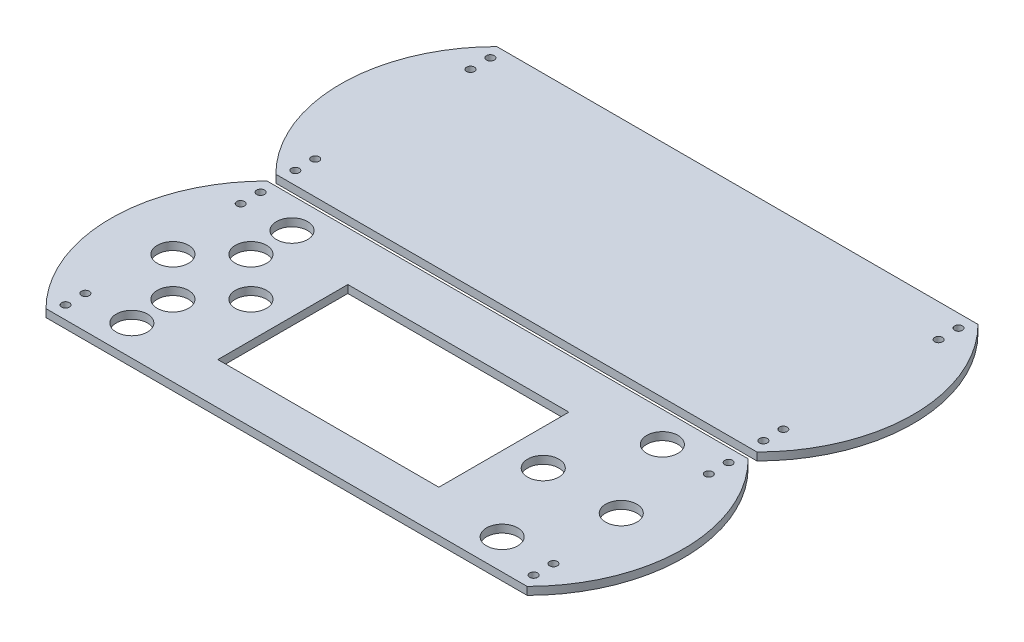
SolidWorks part; units mm, degrees
ref_plane "Front Plane" through (0, 0, 0) normal (0, 0, 1) x (1, 0, 0)
ref_plane "Top Plane" through (0, 0, 0) normal (0, 1, 0) x (1, 0, 0)
ref_plane "Right Plane" through (0, 0, 0) normal (1, 0, 0) x (0, 0, -1)
sketch "Sketch2" plane through (0, 0, 0) normal (0, 1, 0) x (1, 0, 0)
  line L0 (99.1654, 23.5955) -> (99.1654, -51.4045) construction
  line L1 (6.6654, 23.5955) -> (191.6654, 23.5955) construction
  line L2 (191.6654, -51.4045) -> (6.6654, -51.4045) construction
  line L3 (-8.8676, -13.9045) -> (207.1984, -13.9045) construction
  line L4 (6.6654, 23.5955) -> (6.6654, -51.4045) construction
  line L5 (56.6654, 9.6576) -> (141.6654, 9.6576)
  line L6 (56.6654, 9.6576) -> (56.6654, -40.3424)
  line L7 (56.6654, -40.3424) -> (141.6654, -40.3424)
  line L8 (141.6654, 9.6576) -> (141.6654, -40.3424)
  line L9 (191.6654, 23.5955) -> (191.6654, -51.4045) construction
  line L10 (27.9654, -13.9045) -> (27.9654, 23.5955) construction
  line L11 (27.9654, -13.9045) -> (27.9654, -51.4045) construction
  line L12 (6.6654, 28.5955) -> (191.6654, 28.5955)
  line L13 (6.6654, -56.4045) -> (191.6654, -56.4045)
  line L14 (99.1654, 23.5955) -> (99.1654, 28.5955) construction
  line L15 (9.1654, 23.5955) -> (9.1654, -51.4045) construction
  line L16 (-8.8676, -13.9045) -> (-10.9387, -13.9045) construction
  line L17 (98.5966, 112.5389) -> (98.5966, 37.5389) construction
  line L18 (6.0966, 112.5389) -> (191.0966, 112.5389) construction
  line L19 (191.0966, 37.5389) -> (6.0966, 37.5389) construction
  line L20 (-9.4364, 75.0389) -> (206.6296, 75.0389) construction
  line L21 (6.0966, 112.5389) -> (6.0966, 37.5389) construction
  line L26 (191.0966, 112.5389) -> (191.0966, 37.5389) construction
  line L28 (27.3966, 75.0389) -> (27.3966, 37.5389) construction
  line L29 (6.0966, 117.5389) -> (191.0966, 117.5389)
  line L30 (6.0966, 32.5389) -> (191.0966, 32.5389)
  line L31 (98.5966, 112.5389) -> (98.5966, 117.5389) construction
  line L32 (8.5966, 112.5389) -> (8.5966, 37.5389) construction
  line L33 (-9.4364, 75.0389) -> (-11.5075, 75.0389) construction
  arc A0 (6.6654, 28.5955) -> (6.6654, -56.4045) centre (49.1654, -13.9045) ccw
  arc A1 (191.6654, 28.5955) -> (191.6654, -56.4045) centre (149.1654, -13.9045) cw
  circle A2 centre (42.9654, -13.9045) radius 6
  circle A3 centre (12.9654, -13.9045) radius 6
  circle A4 centre (27.9654, 1.0955) radius 6
  circle A5 centre (27.9654, -28.9045) radius 6
  circle A6 centre (155.3654, -13.9045) radius 6
  circle A7 centre (185.3654, -13.9045) radius 6
  circle A8 centre (27.9654, 16.8955) radius 6
  circle A9 centre (27.9654, -44.7045) radius 6
  circle A10 centre (170.3654, -44.7045) radius 6
  circle A11 centre (170.3654, 16.8955) radius 6
  circle A12 centre (9.1654, 23.5955) radius 1.5
  circle A13 centre (189.1654, 23.5955) radius 1.5
  circle A14 centre (189.1654, -51.4045) radius 1.5
  circle A15 centre (9.1654, -51.4045) radius 1.5
  circle A16 centre (9.1654, 15.9594) radius 1.5
  circle A17 centre (9.1654, -43.7684) radius 1.5
  circle A18 centre (189.1654, -43.7684) radius 1.5
  circle A19 centre (189.1654, 15.9594) radius 1.5
  arc A20 (6.0966, 117.5389) -> (6.0966, 32.5389) centre (48.5966, 75.0389) ccw
  arc A21 (191.0966, 117.5389) -> (191.0966, 32.5389) centre (148.5966, 75.0389) cw
  circle A32 centre (8.5966, 112.5389) radius 1.5
  circle A33 centre (188.5966, 112.5389) radius 1.5
  circle A34 centre (188.5966, 37.5389) radius 1.5
  circle A35 centre (8.5966, 37.5389) radius 1.5
  circle A36 centre (8.5966, 104.9028) radius 1.5
  circle A37 centre (8.5966, 45.175) radius 1.5
  circle A38 centre (188.5966, 45.175) radius 1.5
  circle A39 centre (188.5966, 104.9028) radius 1.5
  dimension "D8" = 12
  dimension "D9" = 12
  dimension "D11" = 12
  dimension "D13" = 12
  dimension "D16" = 3
  dimension "D19" = 3
  dimension "D35" = 3
  dimension "D36" = 3
  dimension "D2" = 75
  dimension "D3" = 85
  dimension "D4" = 50
  dimension "D5" = 13.7
  dimension "D6" = 50
  dimension "D7" = 30
  dimension "D10" = 15
  dimension "D12" = 15
  dimension "D14" = 15.8
  dimension "D15" = 5
  dimension "D17" = 90
  dimension "D18" = 185
  dimension "D20" = 29.8639
  dimension "D21" = 75
  dimension "D34" = 5
extrude "Boss-Extrude1" add sketch "Sketch2" along normal blind 3
